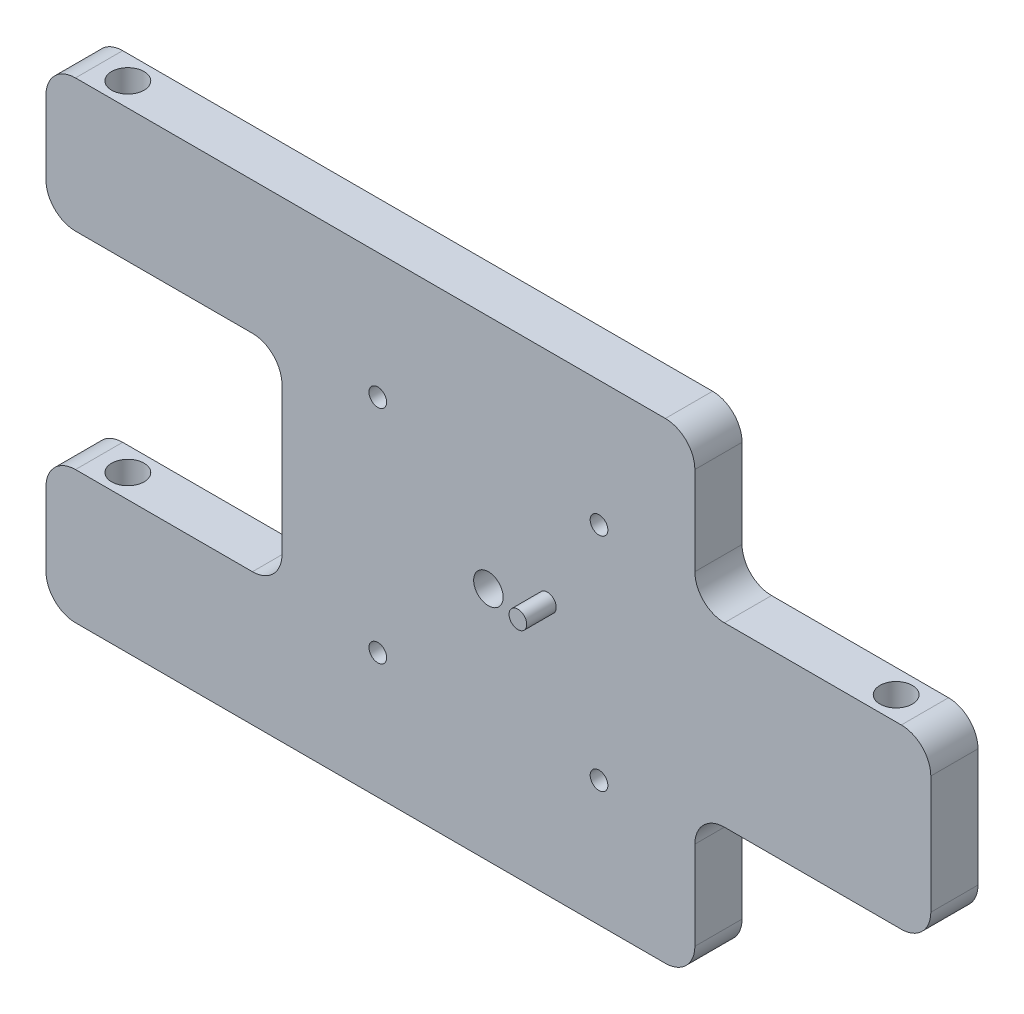
SolidWorks part; units mm, degrees
ref_plane "Front Plane" through (0, 0, 0) normal (0, 0, 1) x (1, 0, 0)
ref_plane "Top Plane" through (0, 0, 0) normal (0, 1, 0) x (1, 0, 0)
ref_plane "Right Plane" through (0, 0, 0) normal (1, 0, 0) x (0, 0, -1)
sketch "Sketch1" plane through (0, 0, 0) normal (0, 1, 0) x (1, 0, 0)
  line L0 (65.125, 0) -> (-65.125, 0) construction
  line L2 (75, -4) -> (-75, -4)
  line L3 (75, -4) -> (75, 4)
  line L4 (75, 4) -> (-75, 4)
  line L5 (-75, -4) -> (-75, 4)
  line L6 (75, -4) -> (-75, 4) construction
  line L7 (75, 4) -> (-75, -4) construction
  circle A0 centre (-65.125, 0) radius 2.75
  circle A1 centre (65.125, 0) radius 2.75
  point P4 (0, 0)
  point P7 (0, 0)
  dimension "D1" = 5.5
  dimension "D2" = 5.5
  dimension "D3" = 130.25
  dimension "D4" = 8
  dimension "D5" = 150
extrude "Boss-Extrude1" add sketch "Sketch1" along normal mid plane 80
sketch "Sketch2" plane through (0, 0, 4) normal (0, 0, 1) x (1, 0, 0)
  line L1 (18.75, -18.75) -> (-18.75, -18.75) construction
  line L2 (18.75, -18.75) -> (18.75, 18.75) construction
  line L3 (18.75, 18.75) -> (-18.75, 18.75) construction
  line L4 (-18.75, -18.75) -> (-18.75, 18.75) construction
  line L5 (18.75, -18.75) -> (-18.75, 18.75) construction
  line L6 (18.75, 18.75) -> (-18.75, -18.75) construction
  circle A0 centre (-18.75, 18.75) radius 1.5
  circle A1 centre (18.75, 18.75) radius 1.5
  circle A2 centre (18.75, -18.75) radius 1.5
  circle A3 centre (-18.75, -18.75) radius 1.5
  point P0 (0, 0)
  dimension "D2" = 3
  dimension "D1" = 37.5
extrude "Cut-Extrude1" cut sketch "Sketch2" against normal through all
sketch "Sketch3" plane through (0, 0, 4) normal (0, 0, 1) x (1, 0, 0)
  line L0 (-75, 17.5) -> (-35, 17.5)
  line L1 (-75, 40) -> (-75, -40) construction
  line L2 (-35, 17.5) -> (-35, -17.5)
  line L3 (-35, -17.5) -> (-75, -17.5)
  line L4 (-75, -17.5) -> (-75, 17.5)
  line L5 (-75, 40) -> (75, 40) construction
  line L6 (75, 40) -> (35, 40)
  line L7 (35, 40) -> (35, 15)
  line L8 (35, 15) -> (75, 15)
  line L9 (75, 40) -> (75, -40) construction
  line L10 (75, 15) -> (75, 40)
  line L11 (-1000, 0) -> (49000, 0) construction
  line L12 (75, -15) -> (75, -40)
  line L13 (35, -15) -> (75, -15)
  line L14 (35, -40) -> (35, -15)
  line L15 (75, -40) -> (35, -40)
  point P4 (-75, 0)
  point P7 (-35, 0)
  dimension "D1" = 40
  dimension "D2" = 35
  dimension "D3" = 40
  dimension "D4" = 25
extrude "Cut-Extrude2" cut sketch "Sketch3" against normal through all
fillet "Fillet1" radius 5 12 edges at (35, 40, 0) (-35, -17.5, 0) (-75, -17.5, 0) (-75, -40, 0) (35, -40, 0) (35, -15, 0) (75, -15, 0) (75, 15, 0) (35, 15, 0) (-35, 17.5, 0) (-75, 17.5, 0) (-75, 40, 0)
sketch "Sketch4" plane through (0, 0, 4) normal (0, 0, 1) x (1, 0, 0)
  circle A0 centre (0, 0) radius 2.5
  dimension "D1" = 5
extrude "Cut-Extrude3" cut sketch "Sketch4" against normal through all
sketch "Sketch5" plane through (0, 0, 4) normal (0, 0, 1) x (1, 0, 0)
  circle A0 centre (10, 3) radius 1.5
  dimension "D1" = 3
  dimension "D2" = 10
  dimension "D3" = 3
extrude "Boss-Extrude2" add sketch "Sketch5" along normal blind 5
